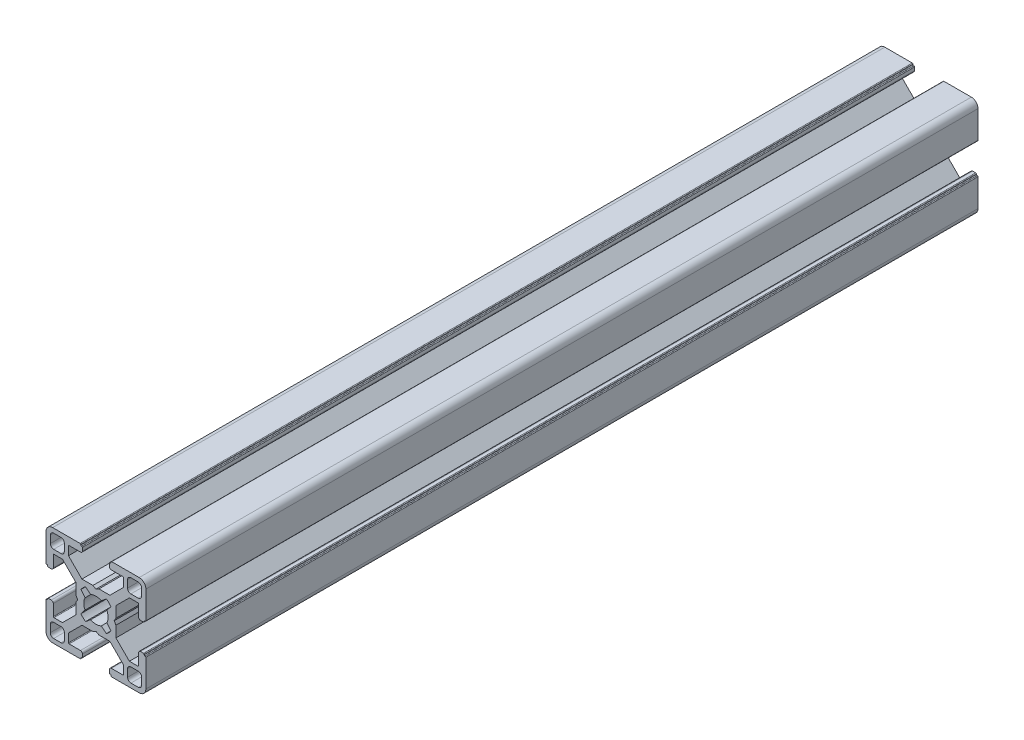
SolidWorks part; units mm, degrees
ref_plane "Front" through (0, 0, 0) normal (0, 0, 1) x (1, 0, 0)
ref_plane "Top" through (0, 0, 0) normal (0, 1, 0) x (1, 0, 0)
ref_plane "Right" through (0, 0, 0) normal (1, 0, 0) x (0, 0, -1)
sketch "Sketch1" plane through (0, 0, 0) normal (0, 0, 1) x (1, 0, 0)
  line L0 (13.7, 12.7) -> (13.7, 10.5)
  line L1 (10.5, 9.5) -> (12.7, 9.5)
  line L2 (9.5, 12.7) -> (9.5, 10.5)
  line L3 (10.5, 13.7) -> (12.7, 13.7)
  line L4 (3.1359, 4.5184) -> (1.6001, 3.2806)
  line L5 (3.2806, 1.6001) -> (4.5053, 3.1547)
  line L6 (6.0045, 0.9) -> (5.4849, 0)
  line L7 (6.0045, 4.2045) -> (6.0045, 0.9)
  line L8 (0, -5.4849) -> (0.9, -6)
  line L9 (0.9, -6) -> (4.2045, -6)
  line L10 (4.2045, -6) -> (8.25, -10.05)
  line L11 (8.25, -10.05) -> (8.25, -12.6)
  line L12 (4.65, -12.8) -> (8.05, -12.8)
  line L13 (4.05, -14.3) -> (4.05, -13.4)
  line L14 (4.25, -14.5) -> (4.35, -14.5)
  line L15 (4.55, -14.8) -> (4.55, -14.7)
  line L16 (4.75, -15) -> (13, -15)
  line L17 (15, -13) -> (15, -4.75)
  line L18 (14.7, -4.55) -> (14.8, -4.55)
  line L19 (14.5, -4.35) -> (14.5, -4.25)
  line L20 (13.4, -4.05) -> (14.3, -4.05)
  line L21 (12.8, -8.05) -> (12.8, -4.65)
  line L22 (12.6, -8.25) -> (10.05, -8.25)
  line L23 (10.05, -8.25) -> (6.0045, -4.2045)
  line L24 (6.0045, -4.2045) -> (6.0045, -0.9)
  line L25 (6.0045, -0.9) -> (5.4849, 0)
  line L26 (10.05, 8.25) -> (6.0045, 4.2045)
  line L27 (12.6, 8.25) -> (10.05, 8.25)
  line L28 (12.8, 8.05) -> (12.8, 4.65)
  line L29 (13.4, 4.05) -> (14.3, 4.05)
  line L30 (14.5, 4.35) -> (14.5, 4.25)
  line L31 (14.7, 4.55) -> (14.8, 4.55)
  line L32 (15, 13) -> (15, 4.75)
  line L33 (4.75, 15) -> (13, 15)
  line L34 (4.55, 14.8) -> (4.55, 14.7)
  line L35 (4.25, 14.5) -> (4.35, 14.5)
  line L36 (4.05, 14.3) -> (4.05, 13.4)
  line L37 (4.65, 12.8) -> (8.05, 12.8)
  line L38 (8.25, 10.05) -> (8.25, 12.6)
  line L39 (4.2045, 6) -> (8.25, 10.05)
  line L40 (0.9, 6) -> (4.2045, 6)
  line L41 (0, 5.4849) -> (0.9, 6)
  line L42 (-13.7, -12.7) -> (-13.7, -10.5)
  line L43 (-10.5, -9.5) -> (-12.7, -9.5)
  line L44 (-9.5, -12.7) -> (-9.5, -10.5)
  line L45 (-10.5, -13.7) -> (-12.7, -13.7)
  line L46 (-3.1359, -4.5184) -> (-1.6001, -3.2806)
  line L47 (-3.2806, -1.6001) -> (-4.5053, -3.1547)
  line L48 (0, 5.4849) -> (-0.9, 6)
  line L49 (-0.9, 6) -> (-4.2045, 6)
  line L50 (-4.2045, 6) -> (-8.25, 10.05)
  line L51 (-8.25, 10.05) -> (-8.25, 12.6)
  line L52 (-4.65, 12.8) -> (-8.05, 12.8)
  line L53 (-4.05, 14.3) -> (-4.05, 13.4)
  line L54 (-4.25, 14.5) -> (-4.35, 14.5)
  line L55 (-4.55, 14.8) -> (-4.55, 14.7)
  line L56 (-4.75, 15) -> (-13, 15)
  line L57 (-15, 13) -> (-15, 4.75)
  line L58 (-14.7, 4.55) -> (-14.8, 4.55)
  line L59 (-14.5, 4.35) -> (-14.5, 4.25)
  line L60 (-13.4, 4.05) -> (-14.3, 4.05)
  line L61 (-12.8, 8.05) -> (-12.8, 4.65)
  line L62 (-12.6, 8.25) -> (-10.05, 8.25)
  line L63 (-10.05, 8.25) -> (-6.0045, 4.2045)
  line L64 (-6.0045, -0.9) -> (-5.4849, 0)
  line L65 (-6.0045, -4.2045) -> (-6.0045, -0.9)
  line L66 (-10.05, -8.25) -> (-6.0045, -4.2045)
  line L67 (-12.6, -8.25) -> (-10.05, -8.25)
  line L68 (-12.8, -8.05) -> (-12.8, -4.65)
  line L69 (-13.4, -4.05) -> (-14.3, -4.05)
  line L70 (-14.5, -4.35) -> (-14.5, -4.25)
  line L71 (-14.7, -4.55) -> (-14.8, -4.55)
  line L72 (-15, -13) -> (-15, -4.75)
  line L73 (-4.75, -15) -> (-13, -15)
  line L74 (-4.55, -14.8) -> (-4.55, -14.7)
  line L75 (-4.25, -14.5) -> (-4.35, -14.5)
  line L76 (-4.05, -14.3) -> (-4.05, -13.4)
  line L77 (3.2806, -1.6001) -> (4.5053, -3.1547)
  line L78 (3.1359, -4.5184) -> (1.6001, -3.2806)
  line L79 (-4.65, -12.8) -> (-8.05, -12.8)
  line L80 (-8.25, -10.05) -> (-8.25, -12.6)
  line L81 (-4.2045, -6) -> (-8.25, -10.05)
  line L82 (-0.9, -6) -> (-4.2045, -6)
  line L83 (0, -5.4849) -> (-0.9, -6)
  line L84 (10.5, -13.7) -> (12.7, -13.7)
  line L85 (9.5, -12.7) -> (9.5, -10.5)
  line L86 (10.5, -9.5) -> (12.7, -9.5)
  line L87 (13.7, -12.7) -> (13.7, -10.5)
  line L88 (-6.0045, 4.2045) -> (-6.0045, 0.9)
  line L89 (-6.0045, 0.9) -> (-5.4849, 0)
  line L90 (-3.2806, 1.6001) -> (-4.5053, 3.1547)
  line L91 (-3.1359, 4.5184) -> (-1.6001, 3.2806)
  line L92 (-10.5, 13.7) -> (-12.7, 13.7)
  line L93 (-9.5, 12.7) -> (-9.5, 10.5)
  line L94 (-10.5, 9.5) -> (-12.7, 9.5)
  line L95 (-13.7, 12.7) -> (-13.7, 10.5)
  line L96 (-23.4857, 0) -> (20.9308, 0) construction
  line L97 (0, 17.9563) -> (0, -17.361) construction
  arc A0 (13.7, 12.7) -> (12.7, 13.7) centre (12.7, 12.7) ccw
  arc A1 (12.7, 9.5) -> (13.7, 10.5) centre (12.7, 10.5) ccw
  arc A2 (9.5, 10.5) -> (10.5, 9.5) centre (10.5, 10.5) ccw
  arc A3 (10.5, 13.7) -> (9.5, 12.7) centre (10.5, 12.7) ccw
  arc A4 (1.6001, 3.2806) -> (-1.6001, 3.2806) centre (0, 0) ccw
  arc A5 (8.25, -12.6) -> (8.05, -12.8) centre (8.05, -12.6) cw
  arc A6 (4.65, -12.8) -> (4.05, -13.4) centre (4.65, -13.4) ccw
  arc A7 (4.05, -14.3) -> (4.25, -14.5) centre (4.25, -14.3) ccw
  arc A8 (4.35, -14.5) -> (4.55, -14.7) centre (4.35, -14.7) cw
  arc A9 (4.55, -14.8) -> (4.75, -15) centre (4.75, -14.8) ccw
  arc A10 (13, -15) -> (15, -13) centre (13, -13) ccw
  arc A11 (15, -4.75) -> (14.8, -4.55) centre (14.8, -4.75) ccw
  arc A12 (14.7, -4.55) -> (14.5, -4.35) centre (14.7, -4.35) cw
  arc A13 (14.5, -4.25) -> (14.3, -4.05) centre (14.3, -4.25) ccw
  arc A14 (13.4, -4.05) -> (12.8, -4.65) centre (13.4, -4.65) ccw
  arc A15 (12.8, -8.05) -> (12.6, -8.25) centre (12.6, -8.05) cw
  arc A16 (4.5053, 3.1547) -> (3.1359, 4.5184) centre (0, 0) ccw
  arc A17 (12.8, 8.05) -> (12.6, 8.25) centre (12.6, 8.05) ccw
  arc A18 (13.4, 4.05) -> (12.8, 4.65) centre (13.4, 4.65) cw
  arc A19 (14.5, 4.25) -> (14.3, 4.05) centre (14.3, 4.25) cw
  arc A20 (14.7, 4.55) -> (14.5, 4.35) centre (14.7, 4.35) ccw
  arc A21 (15, 4.75) -> (14.8, 4.55) centre (14.8, 4.75) cw
  arc A22 (13, 15) -> (15, 13) centre (13, 13) cw
  arc A23 (4.55, 14.8) -> (4.75, 15) centre (4.75, 14.8) cw
  arc A24 (4.35, 14.5) -> (4.55, 14.7) centre (4.35, 14.7) ccw
  arc A25 (4.05, 14.3) -> (4.25, 14.5) centre (4.25, 14.3) cw
  arc A26 (4.65, 12.8) -> (4.05, 13.4) centre (4.65, 13.4) cw
  arc A27 (8.25, 12.6) -> (8.05, 12.8) centre (8.05, 12.6) ccw
  arc A28 (-13.7, -12.7) -> (-12.7, -13.7) centre (-12.7, -12.7) ccw
  arc A29 (-12.7, -9.5) -> (-13.7, -10.5) centre (-12.7, -10.5) ccw
  arc A30 (-9.5, -10.5) -> (-10.5, -9.5) centre (-10.5, -10.5) ccw
  arc A31 (-10.5, -13.7) -> (-9.5, -12.7) centre (-10.5, -12.7) ccw
  arc A32 (-4.5053, -3.1547) -> (-3.1359, -4.5184) centre (0, 0) ccw
  arc A33 (-3.2806, 1.6001) -> (-3.2806, -1.6001) centre (0, 0) ccw
  arc A34 (-8.25, 12.6) -> (-8.05, 12.8) centre (-8.05, 12.6) cw
  arc A35 (-4.65, 12.8) -> (-4.05, 13.4) centre (-4.65, 13.4) ccw
  arc A36 (-4.05, 14.3) -> (-4.25, 14.5) centre (-4.25, 14.3) ccw
  arc A37 (-4.35, 14.5) -> (-4.55, 14.7) centre (-4.35, 14.7) cw
  arc A38 (-4.55, 14.8) -> (-4.75, 15) centre (-4.75, 14.8) ccw
  arc A39 (-13, 15) -> (-15, 13) centre (-13, 13) ccw
  arc A40 (-15, 4.75) -> (-14.8, 4.55) centre (-14.8, 4.75) ccw
  arc A41 (-14.7, 4.55) -> (-14.5, 4.35) centre (-14.7, 4.35) cw
  arc A42 (-14.5, 4.25) -> (-14.3, 4.05) centre (-14.3, 4.25) ccw
  arc A43 (-13.4, 4.05) -> (-12.8, 4.65) centre (-13.4, 4.65) ccw
  arc A44 (-12.8, 8.05) -> (-12.6, 8.25) centre (-12.6, 8.05) cw
  arc A45 (-4.5053, 3.1547) -> (-3.1359, 4.5184) centre (0, 0) cw
  arc A46 (-12.8, -8.05) -> (-12.6, -8.25) centre (-12.6, -8.05) ccw
  arc A47 (-13.4, -4.05) -> (-12.8, -4.65) centre (-13.4, -4.65) cw
  arc A48 (-14.5, -4.25) -> (-14.3, -4.05) centre (-14.3, -4.25) cw
  arc A49 (3.2806, 1.6001) -> (3.2806, -1.6001) centre (0, 0) cw
  arc A50 (4.5053, -3.1547) -> (3.1359, -4.5184) centre (0, 0) cw
  arc A51 (1.6001, -3.2806) -> (-1.6001, -3.2806) centre (0, 0) cw
  arc A52 (-14.7, -4.55) -> (-14.5, -4.35) centre (-14.7, -4.35) ccw
  arc A53 (-15, -4.75) -> (-14.8, -4.55) centre (-14.8, -4.75) cw
  arc A54 (-13, -15) -> (-15, -13) centre (-13, -13) cw
  arc A55 (-4.55, -14.8) -> (-4.75, -15) centre (-4.75, -14.8) cw
  arc A56 (10.5, -13.7) -> (9.5, -12.7) centre (10.5, -12.7) cw
  arc A57 (9.5, -10.5) -> (10.5, -9.5) centre (10.5, -10.5) cw
  arc A58 (12.7, -9.5) -> (13.7, -10.5) centre (12.7, -10.5) cw
  arc A59 (13.7, -12.7) -> (12.7, -13.7) centre (12.7, -12.7) cw
  arc A60 (-4.35, -14.5) -> (-4.55, -14.7) centre (-4.35, -14.7) ccw
  arc A61 (-4.05, -14.3) -> (-4.25, -14.5) centre (-4.25, -14.3) cw
  arc A62 (-4.65, -12.8) -> (-4.05, -13.4) centre (-4.65, -13.4) cw
  arc A63 (-8.25, -12.6) -> (-8.05, -12.8) centre (-8.05, -12.6) ccw
  arc A64 (-10.5, 13.7) -> (-9.5, 12.7) centre (-10.5, 12.7) cw
  arc A65 (-9.5, 10.5) -> (-10.5, 9.5) centre (-10.5, 10.5) cw
  arc A66 (-12.7, 9.5) -> (-13.7, 10.5) centre (-12.7, 10.5) cw
  arc A67 (-13.7, 12.7) -> (-12.7, 13.7) centre (-12.7, 12.7) cw
  point P81 (15, 15)
  point P82 (0, 15)
  point P203 (0, -15)
  point P204 (15, -15)
  point P206 (0, 0)
  point P207 (15, 0)
  point P219 (-15, 0)
  point P220 (-15, -15)
  point P221 (-15, 15)
  dimension "D6" = 7.3
  dimension "D7" = 11
  dimension "D1" = 30
  dimension "D2" = 15
  dimension "D3" = 30
  dimension "D4" = 8.1
  dimension "D5" = 9
  dimension "D8" = 8.1
extrude "Base-Extrude" add sketch "Sketch1" against normal blind 250
